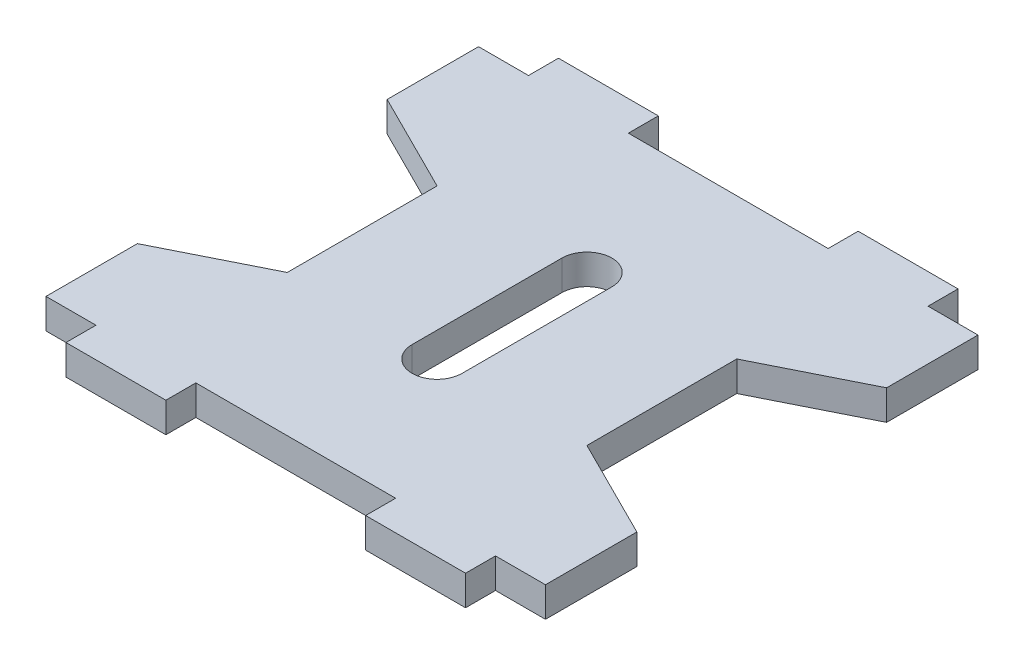
SolidWorks part; units mm, degrees
ref_plane "前视基准面" through (0, 0, 0) normal (0, 0, 1) x (1, 0, 0)
ref_plane "上视基准面" through (0, 0, 0) normal (0, 1, 0) x (1, 0, 0)
ref_plane "右视基准面" through (0, 0, 0) normal (1, 0, 0) x (0, 0, -1)
sketch "草图2" plane through (0, 0, 0) normal (0, 1, 0) x (1, 0, 0)
  line L0 (43.4232, 0) -> (-43.4232, 0) construction
  line L1 (0, 25.8962) -> (0, -25.8962) construction
  line L2 (15, -7.5) -> (15, 7.5)
  line L3 (15, 7.5) -> (25, 12.5)
  line L4 (25, 12.5) -> (25, 21.65)
  line L5 (25, 21.65) -> (20, 21.65)
  line L6 (20, 21.65) -> (20, 24.65)
  line L7 (20, 24.65) -> (10, 24.65)
  line L8 (10, 24.65) -> (10, 21.65)
  line L9 (10, 21.65) -> (-10, 21.65)
  line L10 (-10, 24.65) -> (-10, 21.65)
  line L11 (-20, 24.65) -> (-10, 24.65)
  line L12 (-20, 21.65) -> (-20, 24.65)
  line L13 (-25, 21.65) -> (-20, 21.65)
  line L14 (-25, 12.5) -> (-25, 21.65)
  line L15 (-15, 7.5) -> (-25, 12.5)
  line L16 (-15, -7.5) -> (-15, 7.5)
  line L17 (-15, -7.5) -> (-25, -12.5)
  line L18 (-25, -12.5) -> (-25, -21.65)
  line L19 (-25, -21.65) -> (-20, -21.65)
  line L20 (-20, -21.65) -> (-20, -24.65)
  line L21 (-20, -24.65) -> (-10, -24.65)
  line L22 (-10, -24.65) -> (-10, -21.65)
  line L23 (10, -21.65) -> (-10, -21.65)
  line L24 (10, -24.65) -> (10, -21.65)
  line L25 (20, -24.65) -> (10, -24.65)
  line L26 (20, -21.65) -> (20, -24.65)
  line L27 (25, -21.65) -> (20, -21.65)
  line L28 (25, -12.5) -> (25, -21.65)
  line L29 (15, -7.5) -> (25, -12.5)
  line L30 (-2.5, 7.5) -> (-2.5, -7.5)
  line L31 (2.5, 7.5) -> (2.5, -7.5)
  arc A0 (2.5, 7.5) -> (-2.5, 7.5) centre (0, 7.5) ccw
  arc A1 (2.5, -7.5) -> (-2.5, -7.5) centre (0, -7.5) cw
  point P0 (0, -21.65)
  point P4 (0, 0)
  point P8 (0, 0)
  point P17 (0, 21.65)
  point P25 (-15, 0)
  point P38 (15, 0)
  point P44 (-2.5, 0)
  point P47 (2.5, 0)
  dimension "D1" = 2.5
  dimension "D2" = 15
  dimension "D3" = 3
  dimension "D4" = 50
  dimension "D5" = 43.3
  dimension "D6" = 3
  dimension "D7" = 10
  dimension "D8" = 5
  dimension "D9" = 15
  dimension "D10" = 7.5
  dimension "D11" = 12.5
extrude "凸台-拉伸1" add sketch "草图2" along normal blind 3
